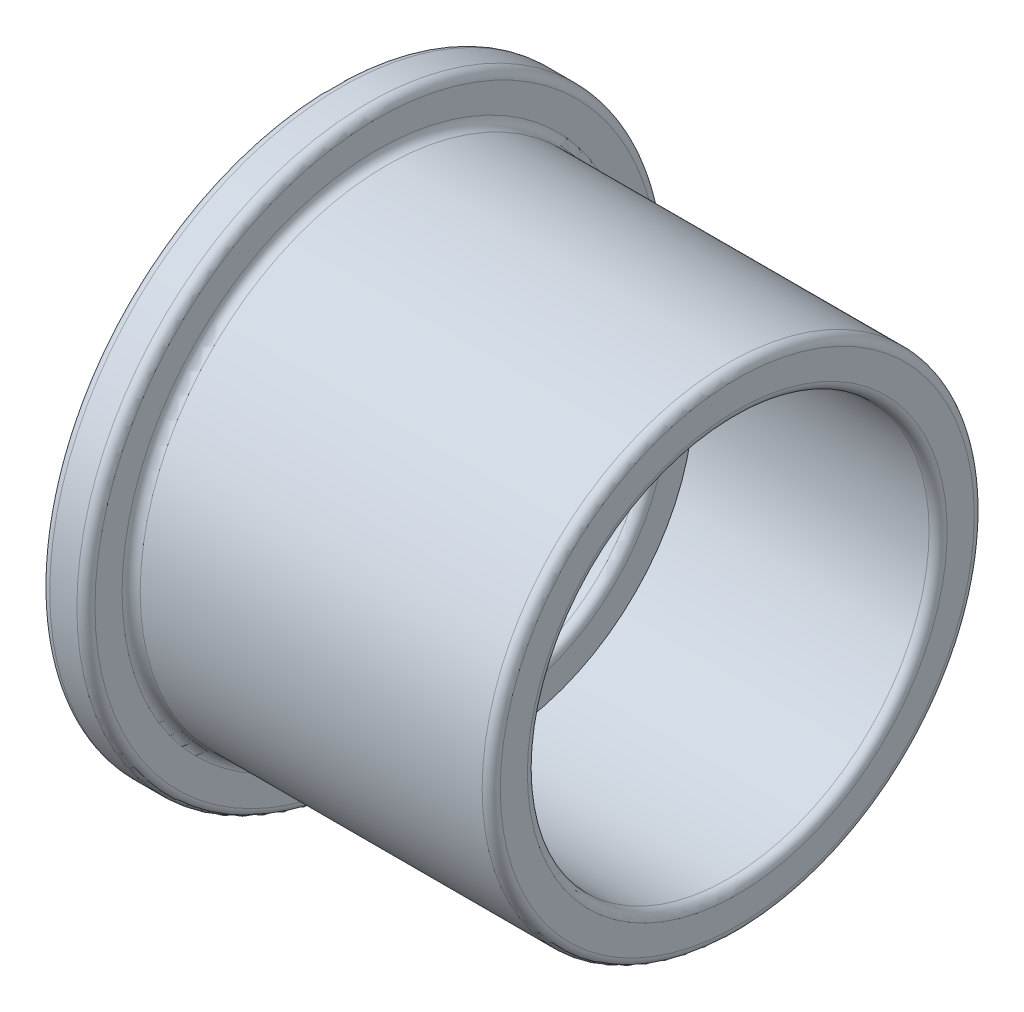
SolidWorks part; units mm, degrees
ref_plane "Front Plane" through (0, 0, 0) normal (0, 0, 1) x (1, 0, 0)
ref_plane "Top Plane" through (0, 0, 0) normal (0, 1, 0) x (1, 0, 0)
ref_plane "Right Plane" through (0, 0, 0) normal (1, 0, 0) x (0, 0, -1)
sketch "Sketch1" plane through (0, 0, 0) normal (0, 0, 1) x (1, 0, 0)
  line L0 (-30.8496, 0) -> (-13.9977, 0) construction
  line L1 (-12.5, 16.1) -> (-12.5, 9.1)
  line L2 (-12.5, 9.1) -> (-3.6, 9.1)
  line L3 (-3.6, 9.1) -> (-3.6, 11.1)
  line L4 (-3.6, 11.1) -> (9.9, 11.1)
  line L5 (9.9, 11.1) -> (9.9, 13.6)
  line L6 (9.9, 13.6) -> (-10, 13.6)
  line L7 (-10, 13.6) -> (-10, 16.1)
  line L8 (-10, 16.1) -> (-12.5, 16.1)
  line L9 (10, 16.1) -> (12.5, 16.1) construction
  line L10 (12.5, 16.1) -> (12.5, 9.1) construction
  line L11 (12.5, 9.1) -> (3.6, 9.1) construction
  line L12 (3.6, 9.1) -> (3.6, 11.1) construction
  line L13 (3.6, 11.1) -> (9.9, 11.1) construction
  line L14 (9.9, 11.1) -> (9.9, 13.6) construction
  line L15 (9.9, 13.6) -> (10, 13.6) construction
  line L16 (10, 13.6) -> (10, 16.1) construction
  line L17 (-3.6, 9.1) -> (3.6, 9.1) construction
  line L18 (-10, 16.1) -> (10, 16.1) construction
  line L19 (0, 0) -> (0, 9.1) construction
  line L20 (0, 16.1) -> (0, 9.1) construction
  dimension "D1" = 20
  dimension "D2" = 2.5
  dimension "D3" = 11.1
  dimension "D4" = 2
  dimension "D5" = 2.5
  dimension "D6" = 2.5
  dimension "D7" = 0.1
  dimension "D8" = 7.2
revolve "Revolve1" add sketch "Sketch1" angle 360 about L0
fillet "Fillet1" radius 0.5 7 edges at (-12.5, 0, 16.1) (-3.6, 0, 9.1) (9.9, 0, 13.6) (9.9, 0, 11.1) (-10, 0, 16.1) (-10, 0, 13.6) (-12.5, 0, 9.1)
